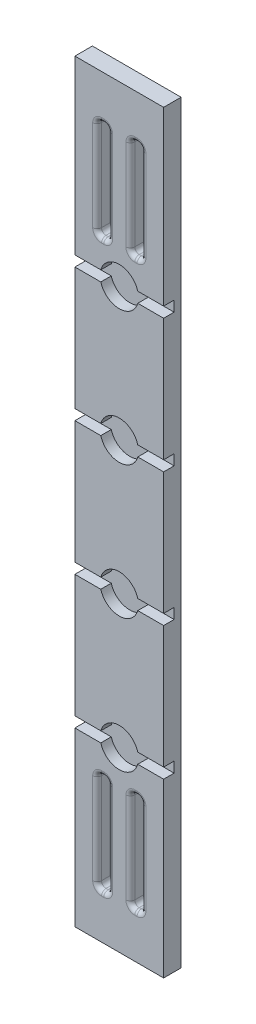
SolidWorks part; units mm, degrees
ref_plane "Front Plane" through (0, 0, 0) normal (0, 0, 1) x (1, 0, 0)
ref_plane "Top Plane" through (0, 0, 0) normal (0, 1, 0) x (1, 0, 0)
ref_plane "Right Plane" through (0, 0, 0) normal (1, 0, 0) x (0, 0, -1)
sketch "Sketch1" plane through (0, 0, 0) normal (0, 0, 1) x (1, 0, 0)
  line L1 (0, 0) -> (25.4, 0)
  line L2 (0, 0) -> (0, 215.9)
  line L3 (0, 215.9) -> (25.4, 215.9)
  line L4 (25.4, 0) -> (25.4, 215.9)
  line L5 (6.35, 203.2) -> (9.525, 203.2)
  line L6 (6.35, 203.2) -> (6.35, 174.625)
  line L7 (6.35, 174.625) -> (9.525, 174.625)
  line L8 (9.525, 203.2) -> (9.525, 174.625)
  line L9 (15.875, 203.2) -> (19.05, 203.2)
  line L10 (15.875, 203.2) -> (15.875, 174.625)
  line L11 (15.875, 174.625) -> (19.05, 174.625)
  line L12 (19.05, 203.2) -> (19.05, 174.625)
  line L13 (6.35, 41.275) -> (9.525, 41.275)
  line L14 (6.35, 41.275) -> (6.35, 12.7)
  line L15 (6.35, 12.7) -> (9.525, 12.7)
  line L16 (9.525, 41.275) -> (9.525, 12.7)
  line L17 (15.875, 41.275) -> (19.05, 41.275)
  line L18 (15.875, 41.275) -> (15.875, 12.7)
  line L19 (15.875, 12.7) -> (19.05, 12.7)
  line L20 (19.05, 41.275) -> (19.05, 12.7)
  dimension "D1" = 25.4
  dimension "D2" = 215.9
  dimension "D3" = 6.35
  dimension "D4" = 6.35
  dimension "D5" = 3.175
  dimension "D6" = 12.7
  dimension "D7" = 28.575
  dimension "D8" = 28.575
  dimension "D9" = 12.7
extrude "Boss-Extrude1" add sketch "Sketch1" along normal blind 5
fillet "Fillet1" radius 1.27 48 edges at (17.4625, 41.275, 5) (17.4625, 41.275, 0) (7.9375, 41.275, 5) (7.9375, 41.275, 0) (19.05, 26.9875, 5) (19.05, 26.9875, 0) (9.525, 26.9875, 5) (9.525, 26.9875, 0) (17.4625, 203.2, 5) (17.4625, 203.2, 0) (7.9375, 203.2, 5) (7.9375, 203.2, 0) (19.05, 188.9125, 5) (19.05, 188.9125, 0) (9.525, 188.9125, 5) (9.525, 188.9125, 0) (15.875, 26.9875, 5) (15.875, 41.275, 2.5) (15.875, 26.9875, 0) (6.35, 26.9875, 5) (6.35, 41.275, 2.5) (6.35, 26.9875, 0) (19.05, 12.7, 2.5) (17.4625, 12.7, 5) (15.875, 12.7, 2.5) (17.4625, 12.7, 0) (9.525, 12.7, 2.5) (7.9375, 12.7, 5) (6.35, 12.7, 2.5) (7.9375, 12.7, 0) (15.875, 188.9125, 5) (15.875, 203.2, 2.5) (15.875, 188.9125, 0) (6.35, 188.9125, 5) (6.35, 203.2, 2.5) (6.35, 188.9125, 0) (19.05, 174.625, 2.5) (17.4625, 174.625, 5) (15.875, 174.625, 2.5) (17.4625, 174.625, 0) (9.525, 174.625, 2.5) (7.9375, 174.625, 5) (6.35, 174.625, 2.5) (7.9375, 174.625, 0) (9.525, 203.2, 2.5) (9.525, 41.275, 2.5) (19.05, 41.275, 2.5) (19.05, 203.2, 2.5)
sketch "Sketch2" plane through (0, 0, 5) normal (0, 0, 1) x (1, 0, 0)
  line L0 (12.7, 215.9) -> (12.7, 165.1) construction
  line L1 (25.4, 215.9) -> (0, 215.9) construction
  line L2 (25.4, 0) -> (25.4, 215.9) construction
  line L3 (17.9915, 166.6) -> (25.4, 166.6)
  line L5 (17.9915, 163.6) -> (25.4, 163.6)
  line L6 (25.4, 166.6) -> (25.4, 163.6)
  line L7 (0, 215.9) -> (0, 0) construction
  line L8 (7.4085, 166.6) -> (0, 166.6)
  line L10 (7.4085, 163.6) -> (0, 163.6)
  line L11 (0, 166.6) -> (0, 163.6)
  line L12 (17.9915, 128.5) -> (25.4, 128.5)
  line L13 (17.9915, 125.5) -> (25.4, 125.5)
  line L14 (25.4, 128.5) -> (25.4, 125.5)
  line L15 (7.4085, 128.5) -> (0, 128.5)
  line L16 (7.4085, 125.5) -> (0, 125.5)
  line L17 (0, 128.5) -> (0, 125.5)
  line L18 (17.9915, 90.4) -> (25.4, 90.4)
  line L19 (17.9915, 87.4) -> (25.4, 87.4)
  line L20 (25.4, 90.4) -> (25.4, 87.4)
  line L21 (7.4085, 90.4) -> (0, 90.4)
  line L22 (7.4085, 87.4) -> (0, 87.4)
  line L23 (0, 90.4) -> (0, 87.4)
  line L24 (17.9915, 52.3) -> (25.4, 52.3)
  line L25 (17.9915, 49.3) -> (25.4, 49.3)
  line L26 (25.4, 52.3) -> (25.4, 49.3)
  line L27 (7.4085, 52.3) -> (0, 52.3)
  line L28 (7.4085, 49.3) -> (0, 49.3)
  line L29 (0, 52.3) -> (0, 49.3)
  arc A0 (7.4085, 163.6) -> (17.9915, 163.6) centre (12.7, 165.1) ccw
  arc A1 (17.9915, 166.6) -> (7.4085, 166.6) centre (12.7, 165.1) ccw
  arc A2 (7.4085, 125.5) -> (17.9915, 125.5) centre (12.7, 127) ccw
  arc A3 (17.9915, 128.5) -> (7.4085, 128.5) centre (12.7, 127) ccw
  arc A4 (7.4085, 87.4) -> (17.9915, 87.4) centre (12.7, 88.9) ccw
  arc A5 (17.9915, 90.4) -> (7.4085, 90.4) centre (12.7, 88.9) ccw
  arc A6 (7.4085, 49.3) -> (17.9915, 49.3) centre (12.7, 50.8) ccw
  arc A7 (17.9915, 52.3) -> (7.4085, 52.3) centre (12.7, 50.8) ccw
  point P1 (0, 165.1)
  point P17 (25.4, 165.1)
  dimension "D1" = 11
  dimension "D2" = 50.8
  dimension "D3" = 3
  dimension "D5" = 38.1
  dimension "D4" = 4
extrude "Cut-Extrude1" cut sketch "Sketch2" against normal blind 3
